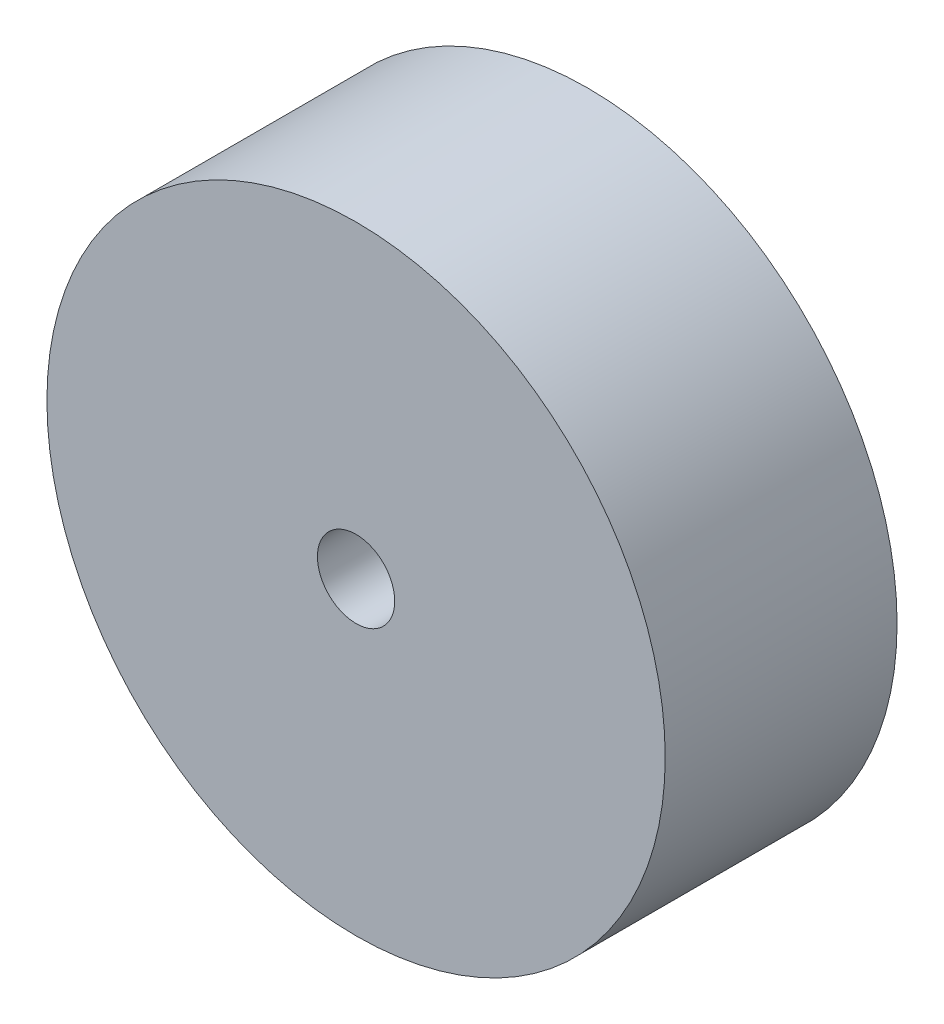
SolidWorks part; units mm, degrees
ref_plane "Front Plane" through (0, 0, 0) normal (0, 0, 1) x (1, 0, 0)
ref_plane "Top Plane" through (0, 0, 0) normal (0, 1, 0) x (1, 0, 0)
ref_plane "Right Plane" through (0, 0, 0) normal (1, 0, 0) x (0, 0, -1)
sketch "Sketch1" plane through (0, 0, 0) normal (0, 0, 1) x (1, 0, 0)
  circle A0 centre (0, 0) radius 101.6
  dimension "D1" = 203.2
extrude "Boss-Extrude1" add sketch "Sketch1" against normal blind 76.2 contours A0
sketch "Sketch2" plane through (0, 0, 0) normal (0, 0, 1) x (1, 0, 0)
  circle A0 centre (0, 0) radius 12.7
  dimension "D1" = 25.4
extrude "Cut-Extrude1" cut sketch "Sketch2" against normal through all both and the other way through all
